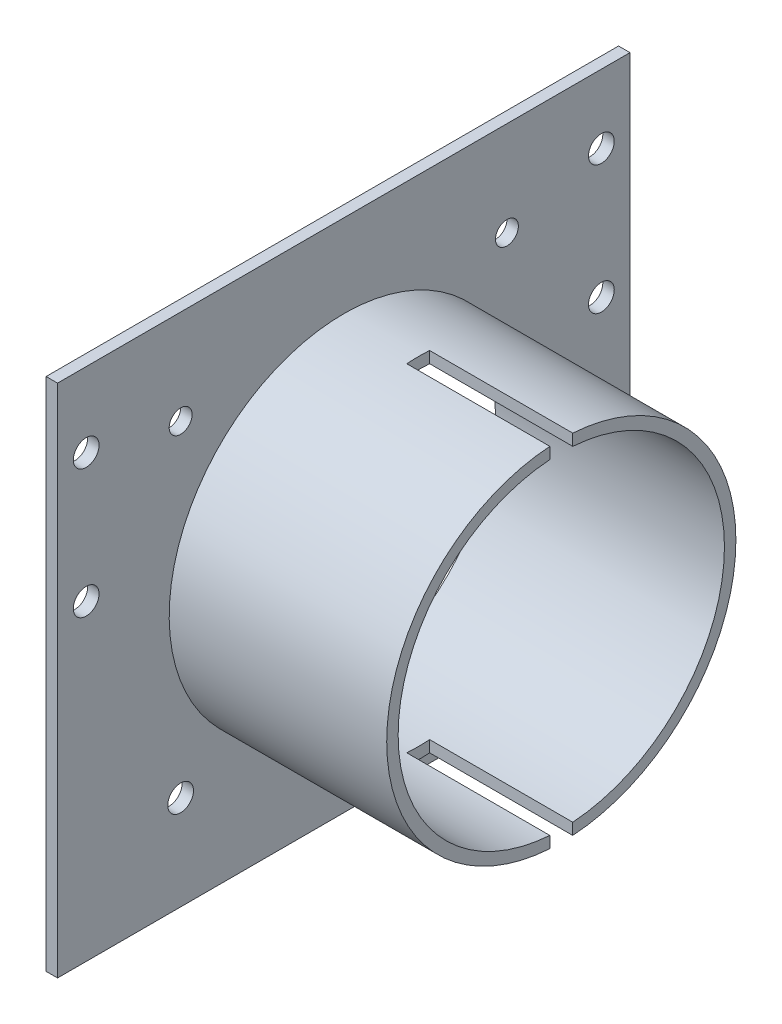
SolidWorks part; units mm, degrees
material "PVC Rígido"
ref_plane "Alzado" through (0, 0, 0) normal (0, 0, 1) x (1, 0, 0)
ref_plane "Planta" through (0, 0, 0) normal (0, 1, 0) x (1, 0, 0)
ref_plane "Vista lateral" through (0, 0, 0) normal (1, 0, 0) x (0, 0, -1)
sketch "Croquis1" plane through (0, 0, 0) normal (1, 0, 0) x (0, 0, -1)
  line L0 (0, 90) -> (0, -90) construction
  line L1 (-100, 90) -> (100, 90)
  line L2 (-100, 90) -> (-100, -90)
  line L3 (-100, -90) -> (100, -90)
  line L4 (100, 90) -> (100, -90)
  line L5 (-100, 90) -> (100, -90) construction
  line L6 (-100, -90) -> (100, 90) construction
  line L7 (57, -57) -> (-57, -57) construction
  line L8 (57, -57) -> (57, 57) construction
  line L9 (57, 57) -> (-57, 57) construction
  line L10 (-57, -57) -> (-57, 57) construction
  line L11 (57, -57) -> (-57, 57) construction
  line L12 (57, 57) -> (-57, -57) construction
  line L13 (-100, 0) -> (100, 0) construction
  circle A0 centre (0, 0) radius 57
  circle A1 centre (-57, 57) radius 4
  circle A2 centre (57, 57) radius 4
  circle A3 centre (57, -57) radius 4
  circle A4 centre (-57, -57) radius 4
  point P0 (0, 0)
  dimension "D2" = 180
  dimension "D1" = 200
extrude "Saliente-Extruir1" add sketch "Croquis1" along normal blind 4
sketch "Croquis2" plane through (4, 0, 0) normal (1, 0, 0) x (0, 0, -1)
  circle A0 centre (0, 0) radius 57
  circle A1 centre (0, 0) radius 61
  dimension "D1" = 4
extrude "Saliente-Extruir2" add sketch "Croquis2" along normal blind 76
sketch "Croquis3" plane through (80, 0, 0) normal (1, 0, 0) x (0, 0, -1)
  line L0 (-57, 0) -> (57, 0) construction
  line L1 (4, -68.5818) -> (-4, -45.4182) construction
  line L2 (4, 45.4182) -> (-4, 45.4182)
  line L3 (4, 45.4182) -> (4, 68.5818)
  line L4 (4, 68.5818) -> (-4, 68.5818)
  line L5 (-4, 45.4182) -> (-4, 68.5818)
  line L6 (4, 45.4182) -> (-4, 68.5818) construction
  line L7 (4, 68.5818) -> (-4, 45.4182) construction
  line L8 (4, -45.4182) -> (-4, -68.5818) construction
  line L9 (-4, -45.4182) -> (-4, -68.5818)
  line L10 (4, -68.5818) -> (-4, -68.5818)
  line L11 (4, -45.4182) -> (-4, -45.4182)
  line L12 (4, -45.4182) -> (4, -68.5818)
  circle A0 centre (0, 0) radius 57 construction
  point P5 (0, 57)
  point P14 (0, -57)
  dimension "D1" = 8
extrude "Cortar-Extruir1" cut sketch "Croquis3" against normal blind 50
hole_wizard "Taladro de margen para M81" positions "Croquis4" profile "Croquis5" hole size "M8" standard "Ansi Metric"
sketch "Croquis4" plane through (4, -7.4173, -252.7608) normal (1, 0, 0) x (0, 0, -1)
  point P0 (-342.7608, 71.4173)
  point P3 (-342.7608, 26.4173)
  point P6 (-162.7608, 73.4147)
  point P9 (-162.7608, 28.4147)
  point P12 (-195.7608, -49.5827)
  point P15 (-309.7608, -49.5827)
sketch "Croquis5" plane through (4, 64, 90) normal (0, 1, 0) x (0, 0, -1)
  line L0 (0, 0) -> (0, 4.999)
  line L1 (0, 4.999) -> (4.5, 4.999)
  line L2 (4.5, 4.999) -> (4.5, 0)
  line L5 (4.5, 0) -> (0, 0)
  line L11 (0, -6.35) -> (0, 107.95) construction
  dimension "Diámetro de taladro hasta el siguiente" = 9
  dimension "Profundidad de taladro hasta el siguiente" = 4.999
